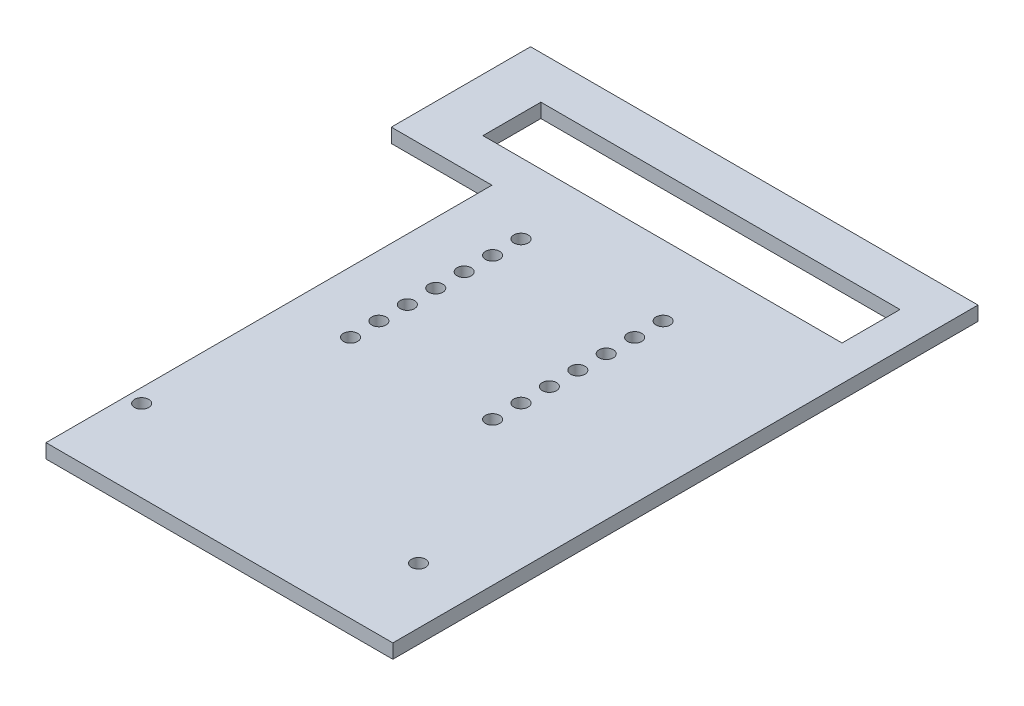
SolidWorks part; units mm, degrees
ref_plane "Front Plane" through (0, 0, 0) normal (0, 0, 1) x (1, 0, 0)
ref_plane "Top Plane" through (0, 0, 0) normal (0, 1, 0) x (1, 0, 0)
ref_plane "Right Plane" through (0, 0, 0) normal (1, 0, 0) x (0, 0, -1)
sketch "Sketch1" plane through (0, 0, 0) normal (0, 1, 0) x (1, 0, 0)
  line L0 (0, -112.5) -> (0, 0) construction
  line L1 (-80, 112.5) -> (100, 112.5)
  line L3 (-80, -112.5) -> (100, -112.5)
  line L4 (100, 112.5) -> (100, -112.5)
  line L5 (0, 0) -> (0, 112.5) construction
  arc A0 (-80, 112.5) -> (-80, -112.5) centre (-80, 0) ccw
  dimension "D1" = 100
  dimension "D4" = 112.5
  dimension "D2" = 80
  dimension "D3" = 225
extrude "Boss-Extrude1" add sketch "Sketch1" against normal blind 3.175
sketch "Sketch2" plane through (0, 0, 0) normal (0, 1, 0) x (1, 0, 0)
  line L0 (36.144, -74.2188) -> (36.144, -67.8688) construction
  line L1 (52.019, 0) -> (52.019, -89.9668) construction
  line L2 (11.887, -89.9668) -> (92.151, -89.9668)
  line L3 (11.887, -89.9668) -> (11.887, -102.9208)
  line L4 (11.887, -102.9208) -> (92.151, -102.9208)
  line L5 (92.151, -89.9668) -> (92.151, -102.9208)
  line L6 (11.887, 89.9668) -> (92.151, 89.9668)
  line L7 (11.887, 89.9668) -> (11.887, 102.9208)
  line L8 (11.887, 102.9208) -> (92.151, 102.9208)
  line L9 (92.151, 89.9668) -> (92.151, 102.9208)
  line L10 (52.019, 0) -> (52.019, 89.9668) construction
  line L11 (36.144, -67.8688) -> (36.144, -61.5188) construction
  line L12 (36.144, -61.5188) -> (36.144, -55.1688) construction
  line L13 (36.144, -55.1688) -> (36.144, -48.8188) construction
  line L14 (36.144, -48.8188) -> (36.144, -42.4688) construction
  line L15 (36.144, -42.4688) -> (36.144, -36.1188) construction
  line L16 (67.894, -74.2188) -> (67.894, -67.8688) construction
  line L17 (67.894, -67.8688) -> (67.894, -61.5188) construction
  line L18 (67.894, -61.5188) -> (67.894, -55.1688) construction
  line L19 (67.894, -55.1688) -> (67.894, -48.8188) construction
  line L20 (67.894, -48.8188) -> (67.894, -42.4688) construction
  line L21 (67.894, -42.4688) -> (67.894, -36.1188) construction
  line L22 (36.144, -74.2188) -> (67.894, -74.2188) construction
  line L23 (36.144, -36.1188) -> (67.894, -36.1188) construction
  line L24 (36.144, 36.1188) -> (36.144, 42.4688) construction
  line L25 (36.144, 42.4688) -> (36.144, 48.8188) construction
  line L26 (36.144, 48.8188) -> (36.144, 55.1688) construction
  line L27 (36.144, 55.1688) -> (36.144, 61.5188) construction
  line L28 (36.144, 61.5188) -> (36.144, 67.8688) construction
  line L29 (36.144, 67.8688) -> (36.144, 74.2188) construction
  line L30 (67.894, 36.1188) -> (67.894, 42.4688) construction
  line L31 (67.894, 42.4688) -> (67.894, 48.8188) construction
  line L32 (67.894, 48.8188) -> (67.894, 55.1688) construction
  line L33 (67.894, 55.1688) -> (67.894, 61.5188) construction
  line L34 (67.894, 61.5188) -> (67.894, 67.8688) construction
  line L35 (67.894, 67.8688) -> (67.894, 74.2188) construction
  line L36 (36.144, 74.2188) -> (67.894, 74.2188) construction
  line L37 (36.144, 36.1188) -> (67.894, 36.1188) construction
  line L38 (36.144, 55.1688) -> (52.019, 55.1688) construction
  line L39 (52.019, 55.1688) -> (67.894, 55.1688) construction
  line L40 (0, -112.5) -> (0, 112.5) construction
  line L41 (0, 0) -> (52.019, 0) construction
  line L42 (100, 112.5) -> (-80, 112.5) construction
  line L43 (-80, -112.5) -> (100, -112.5) construction
  circle A1 centre (36.144, -74.2188) radius 1.5875
  circle A2 centre (36.144, -67.8688) radius 1.5875
  circle A3 centre (36.144, -61.5188) radius 1.5875
  circle A4 centre (36.144, -55.1688) radius 1.5875
  circle A5 centre (36.144, -48.8188) radius 1.5875
  circle A6 centre (36.144, -42.4688) radius 1.5875
  circle A7 centre (36.144, -36.1188) radius 1.5875
  circle A8 centre (67.894, -74.2188) radius 1.5875
  circle A9 centre (67.894, -67.8688) radius 1.5875
  circle A10 centre (67.894, -61.5188) radius 1.5875
  circle A11 centre (67.894, -55.1688) radius 1.5875
  circle A12 centre (67.894, -48.8188) radius 1.5875
  circle A13 centre (67.894, -42.4688) radius 1.5875
  circle A14 centre (67.894, -36.1188) radius 1.5875
  circle A15 centre (36.144, 74.2188) radius 1.5875
  circle A16 centre (36.144, 67.8688) radius 1.5875
  circle A17 centre (36.144, 61.5188) radius 1.5875
  circle A18 centre (36.144, 55.1688) radius 1.5875
  circle A19 centre (36.144, 48.8188) radius 1.5875
  circle A20 centre (36.144, 42.4688) radius 1.5875
  circle A21 centre (36.144, 36.1188) radius 1.5875
  circle A22 centre (67.894, 74.2188) radius 1.5875
  circle A23 centre (67.894, 67.8688) radius 1.5875
  circle A24 centre (67.894, 61.5188) radius 1.5875
  circle A25 centre (67.894, 55.1688) radius 1.5875
  circle A26 centre (67.894, 48.8188) radius 1.5875
  circle A27 centre (67.894, 42.4688) radius 1.5875
  circle A28 centre (67.894, 36.1188) radius 1.5875
  dimension "D6" = 3.175
  dimension "D7" = 6.35
  dimension "D8" = 15.875
  dimension "D10" = 3.175
  dimension "D1" = 12.954
  dimension "D2" = 80.264
  dimension "D3" = 179.9336
  dimension "D4" = 15.748
  dimension "D5" = 15.875
  dimension "D9" = 15.875
  dimension "D11" = 6.35
  dimension "D12" = 15.748
  dimension "D13" = 72.2376
  dimension "D14" = 205.8416
  dimension "D15" = 92.151
extrude "Cut-Extrude1" cut sketch "Sketch2" against normal through all
ref_plane "Plane1" through (92.151, 0, -89.9668) normal (1, 0, 0) x (0, 0, -1)
sketch "Sketch7" plane through (0, 0, 0) normal (0, 1, 0) x (1, 0, 0)
  line L0 (10, 112.5) -> (9.5239, 69.215) construction
  line L1 (-37.4661, 69.215) -> (9.5239, 69.215)
  line L2 (-37.4661, 69.215) -> (-37.4661, -69.215)
  line L3 (-37.4661, -69.215) -> (9.5239, -69.215)
  line L4 (9.5239, 69.215) -> (9.5239, -69.215)
  line L5 (100, 112.5) -> (-80, 112.5) construction
  line L6 (9.5239, -69.215) -> (10, -112.5) construction
  line L7 (-80, -112.5) -> (100, -112.5) construction
  circle A0 centre (-50.1661, 0) radius 1.5875
  circle A1 centre (25.5828, 0) radius 1.5875
  circle A2 centre (87.4621, 0) radius 1.5875
  dimension "D3" = 3.175
  dimension "D1" = 46.99
  dimension "D2" = 138.43
  dimension "D4" = 12.7
extrude "Cut-Extrude4" cut sketch "Sketch7" against normal through all
sketch "Sketch8" plane through (0, 0, 0) normal (0, 1, 0) x (1, 0, 0)
  line L0 (-80, 112.5) -> (-80, -112.5) construction
  line L1 (-192.5, 0) -> (100, 0) construction
  line L2 (100, -112.5) -> (100, 112.5) construction
  line L3 (-167.0966, 25.4) -> (-229.7767, 25.4)
  line L4 (-229.7767, 25.4) -> (-229.7767, -25.4)
  line L5 (-229.7767, -25.4) -> (-167.0966, -25.4)
  arc A0 (-80, 112.5) -> (-80, -112.5) centre (-80, 0) ccw construction
  arc A2 (-167.0966, 25.4) -> (-167.0966, -25.4) centre (-167.0966, 0) cw
  point P12 (-80, 0)
  dimension "D2" = 87.0966
  dimension "D1" = 25.4
extrude "Cut-Extrude5" cut sketch "Sketch8" against normal through all
sketch "Sketch9" plane through (0, 0, 0) normal (0, 1, 0) x (1, 0, 0)
  line L0 (-202.4961, 81.3756) -> (-202.4961, 118.6063)
  line L1 (-202.4961, 81.3756) -> (-202.4961, -78.7163)
  line L2 (-202.4961, 118.6063) -> (0, 118.6063)
  line L3 (22.4836, -78.7163) -> (22.4836, 81.3756)
  line L4 (0, 118.6063) -> (0, 81.3756)
  line L5 (0, 81.3756) -> (22.4836, 81.3756)
  line L6 (-202.4961, -78.7163) -> (-202.4961, -122.3294)
  line L7 (-202.4961, -122.3294) -> (0, -122.3294)
  line L8 (0, -122.3294) -> (0, -78.7163)
  line L9 (0, -78.7163) -> (22.4836, -78.7163)
extrude "Cut-Extrude8" cut sketch "Sketch9" against normal through all
sketch "Sketch10" plane through (0, 0, 0) normal (0, 1, 0) x (1, 0, 0)
  line L1 (-71.9286, -18.2795) -> (148.9824, -18.2795)
  line L2 (-71.9286, -18.2795) -> (-71.9286, -140.5402)
  line L3 (-71.9286, -140.5402) -> (148.9824, -140.5402)
  line L4 (148.9824, -18.2795) -> (148.9824, -140.5402)
extrude "Cut-Extrude9" cut sketch "Sketch10" against normal through all
